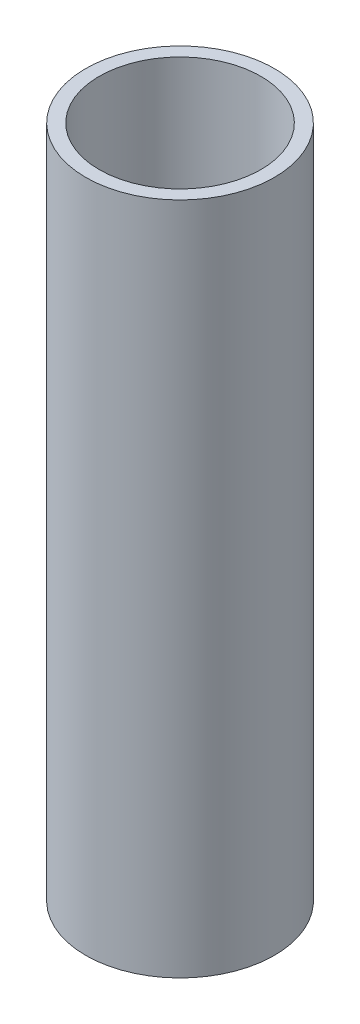
SolidWorks part; units mm, degrees
ref_plane "Front Plane" through (0, 0, 0) normal (0, 0, 1) x (1, 0, 0)
ref_plane "Top Plane" through (0, 0, 0) normal (0, 1, 0) x (1, 0, 0)
ref_plane "Right Plane" through (0, 0, 0) normal (1, 0, 0) x (0, 0, -1)
sketch "Sketch2" plane through (0, 0, 0) normal (0, 1, 0) x (1, 0, 0)
  circle A0 centre (0, 0) radius 3.5
  circle A1 centre (0, 0) radius 3
  dimension "D1" = 7
  dimension "D2" = 6
extrude "Boss-Extrude1" add sketch "Sketch2" along normal blind 25
